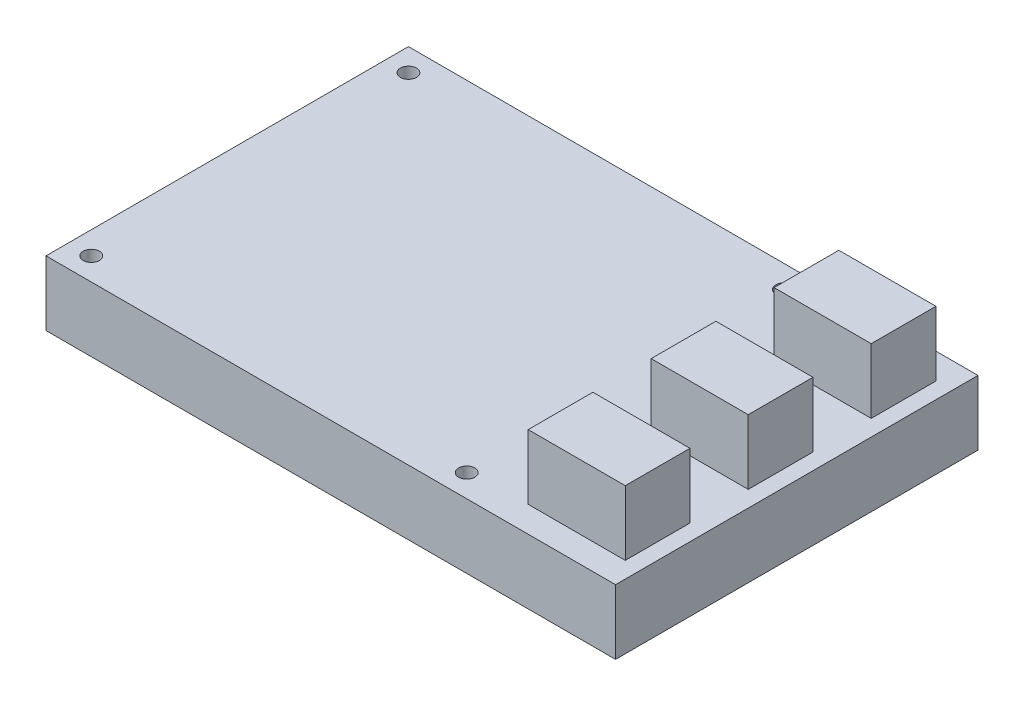
SolidWorks part; units mm, degrees
ref_plane "Front Plane" through (0, 0, 0) normal (0, 0, 1) x (1, 0, 0)
ref_plane "Top Plane" through (0, 0, 0) normal (0, 1, 0) x (1, 0, 0)
ref_plane "Right Plane" through (0, 0, 0) normal (1, 0, 0) x (0, 0, -1)
sketch "Sketch1" plane through (0, 0, 0) normal (0, 1, 0) x (1, 0, 0)
  line L1 (-44, 28) -> (44, 28)
  line L2 (-44, 28) -> (-44, -28)
  line L3 (-44, -28) -> (44, -28)
  line L4 (44, 28) -> (44, -28)
  line L5 (-44, 28) -> (44, -28) construction
  line L6 (-44, -28) -> (44, 28) construction
  point P0 (0, 0)
  dimension "D1" = 88
  dimension "D2" = 56
extrude "Boss-Extrude2" add sketch "Sketch1" along normal blind 10
sketch "Sketch2" plane through (0, 10, 0) normal (0, 1, 0) x (1, 0, 0)
  line L0 (-44, 28) -> (-44, -28) construction
  line L1 (44, 28) -> (-44, 28) construction
  circle A0 centre (-40.5, 24.5) radius 1.25
  circle A1 centre (17.5, 24.5) radius 1.25
  circle A2 centre (-40.5, -24.5) radius 1.25
  circle A3 centre (17.5, -24.5) radius 1.25
  dimension "D1" = 2.5
  dimension "D2" = 3.5
  dimension "D3" = 3.5
  dimension "D4" = 58
  dimension "D5" = 49
extrude "Cut-Extrude1" cut sketch "Sketch2" against normal blind 10
sketch "Sketch3" plane through (0, 10, 0) normal (0, 1, 0) x (1, 0, 0)
  line L0 (44, 28) -> (-44, 28) construction
  line L1 (26.5, 24) -> (41.5, 24)
  line L2 (26.5, 24) -> (26.5, 14)
  line L3 (26.5, 14) -> (41.5, 14)
  line L4 (41.5, 24) -> (41.5, 14)
  line L5 (26.5, 24) -> (41.5, 14) construction
  line L6 (26.5, 14) -> (41.5, 24) construction
  line L7 (26.5, 5) -> (41.5, 5)
  line L8 (26.5, 5) -> (26.5, -5)
  line L9 (26.5, -5) -> (41.5, -5)
  line L10 (41.5, 5) -> (41.5, -5)
  line L11 (26.5, 5) -> (41.5, -5) construction
  line L12 (26.5, -5) -> (41.5, 5) construction
  line L13 (26.5, -14) -> (41.5, -14)
  line L14 (26.5, -14) -> (26.5, -24)
  line L15 (26.5, -24) -> (41.5, -24)
  line L16 (41.5, -14) -> (41.5, -24)
  line L17 (26.5, -14) -> (41.5, -24) construction
  line L18 (26.5, -24) -> (41.5, -14) construction
  line L19 (44, -28) -> (44, 28) construction
  point P0 (34, 19)
  point P5 (34, 0)
  point P10 (34, -19)
  dimension "D1" = 15
  dimension "D2" = 10
  dimension "D3" = 9
  dimension "D4" = 10
  dimension "D5" = 19
  dimension "D6" = 19
extrude "Boss-Extrude3" add sketch "Sketch3" along normal blind 10
